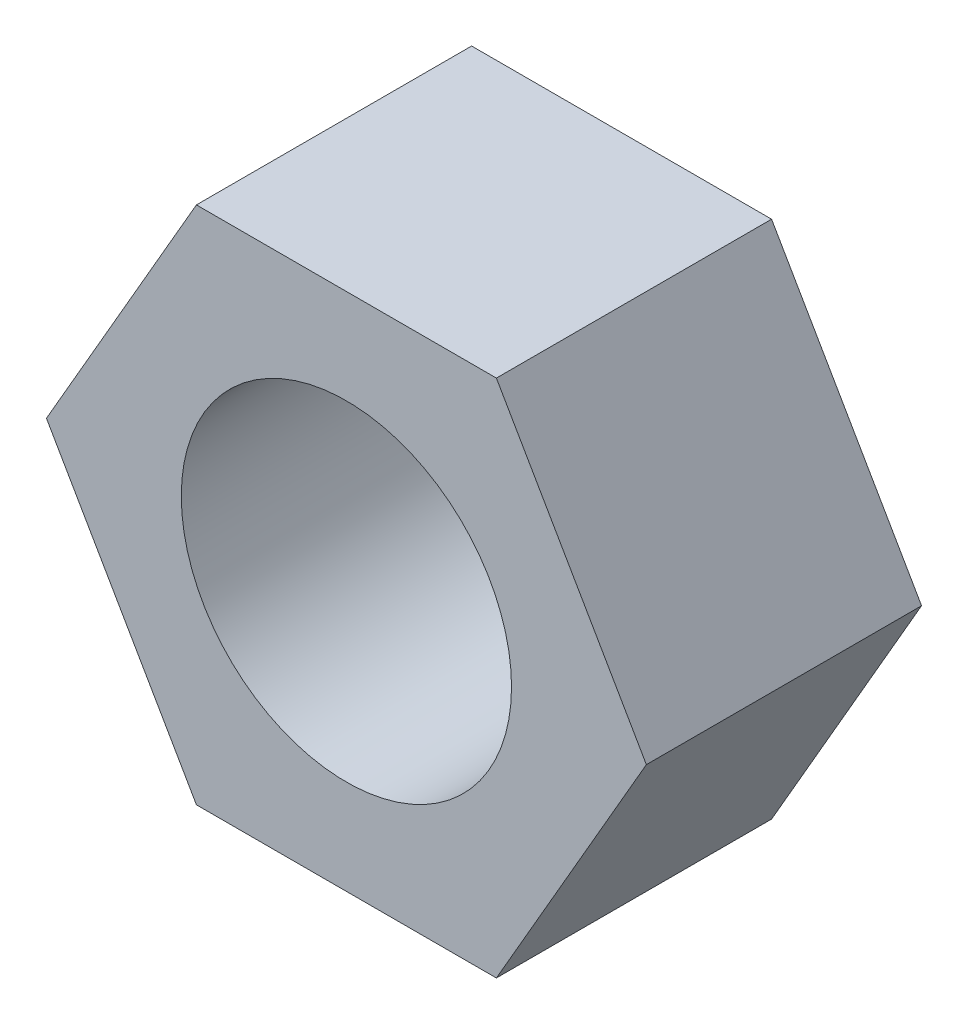
SolidWorks part; units mm, degrees
material "Plain Carbon Steel"
ref_plane "Спереди" through (0, 0, 0) normal (0, 0, 1) x (1, 0, 0)
ref_plane "Сверху" through (0, 0, 0) normal (0, 1, 0) x (1, 0, 0)
ref_plane "Справа" through (0, 0, 0) normal (1, 0, 0) x (0, 0, -1)
sketch "Sketch1" plane through (0, 0, 0) normal (0, 0, 1) x (1, 0, 0)
  line L1 (5.45, 0) -> (2.725, 4.7198)
  line L2 (2.725, 4.7198) -> (-2.725, 4.7198)
  line L3 (-2.725, 4.7198) -> (-5.45, 0)
  line L4 (-5.45, 0) -> (-2.725, -4.7198)
  line L5 (-2.725, -4.7198) -> (2.725, -4.7198)
  line L6 (2.725, -4.7198) -> (5.45, 0)
  circle A0 centre (0, 0) radius 4.7198 construction
  circle A1 centre (0, 0) radius 3
  dimension "D1" = 6
  dimension "D2" = 10.9
extrude "Boss-Extrude1" add sketch "Sketch1" along normal blind 5
